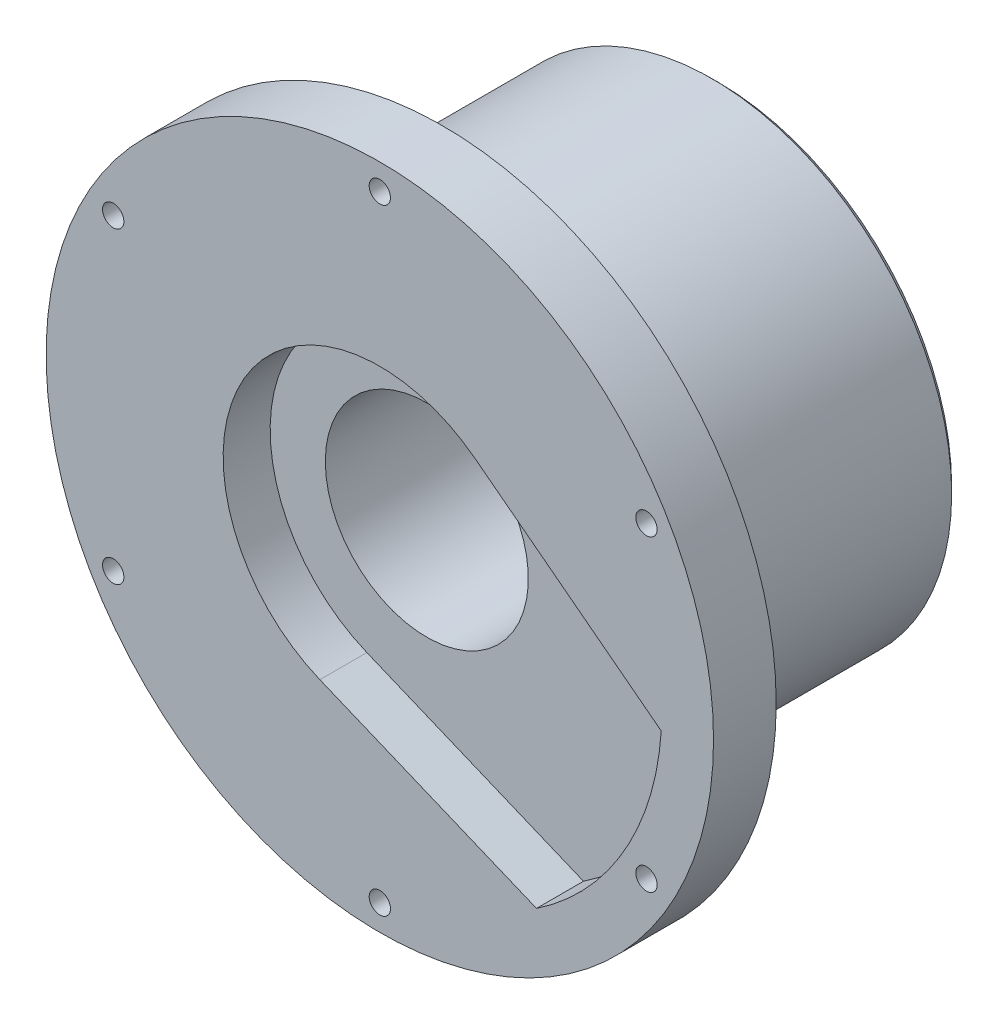
SolidWorks part; units mm, degrees
material "PLA – 15% infill – 2 walls"
ref_plane "Front Plane" through (0, 0, 0) normal (0, 0, 1) x (1, 0, 0)
ref_plane "Top Plane" through (0, 0, 0) normal (0, 1, 0) x (1, 0, 0)
ref_plane "Right Plane" through (0, 0, 0) normal (1, 0, 0) x (0, 0, -1)
sketch "Sketch1" plane through (0, 0, 0) normal (0, 0, 1) x (1, 0, 0)
  circle A0 centre (0, 0) radius 53.25
  dimension "D1" = 106.5
extrude "Boss-Extrude1" add sketch "Sketch1" along normal mid plane 54
sketch "Sketch2" plane through (0, 0, -27) normal (0, 0, -1) x (-1, 0, 0)
  circle A0 centre (0, 0) radius 38.25
  dimension "D1" = 76.5
extrude "Cut-Extrude1" cut sketch "Sketch2" against normal offset from surface (44 mm away) 10 flip side to cut up to face at (53.25, 0, 27)
sketch "Sketch3" plane through (0, 0, 27) normal (0, 0, 1) x (1, 0, 0)
  circle A0 centre (0, 0) radius 49.125 construction
  point P0 (0, 49.125)
  dimension "D1" = 98.25
hole_wizard "M3 Clearance Hole2" positions "Sketch3" profile "Sketch4" hole size "M3" standard "ANSI Metric" end condition through all
sketch "Sketch4" plane through (0, 49.125, 27) normal (1, 0, 0) x (0, -1, 0)
  line L0 (0, 0) -> (0, 54)
  line L1 (0, 54) -> (1.7, 54)
  line L2 (1.7, 54) -> (1.7, 0)
  line L5 (1.7, 0) -> (0, 0)
  line L11 (0, -6.35) -> (0, 107.95) construction
  dimension "Thru Hole Dia." = 3.4
  dimension "Thru Hole Depth" = 54
pattern_circular "CirPattern1" count 6 over 360 about axis through (0, 0, 0) along (0, 0, 1) of "M3 Clearance Hole2"
sketch "Sketch6" plane through (0, 0, 0) normal (1, 0, 0) x (0, 0, -1)
  line L0 (27, 0) -> (-27, 0)
  line L1 (27, 0) -> (27, 9.7)
  line L2 (27, -38.25) -> (27, 38.25) construction
  line L3 (27, 9.7) -> (21, 9.7)
  line L4 (21, 9.7) -> (21, 16.2)
  line L5 (21, 16.2) -> (-27, 16.2)
  line L6 (-27, 53.25) -> (-27, -53.25) construction
  line L7 (-27, 16.2) -> (-27, 0)
  dimension "D1" = 16.2
  dimension "D2" = 6
  dimension "D3" = 9.7
revolve "Cut-Revolve1" cut sketch "Sketch6" angle 360 about L0
sketch "Sketch7" plane through (0, 0, -27) normal (0, 0, -1) x (-1, 0, 0)
  circle A0 centre (0, 0) radius 13 construction
  point P27 (0, 13)
  dimension "D1" = 26
sketch "Sketch11" plane through (0, 0, 27) normal (0, 0, 1) x (1, 0, 0)
  line L1 (0, 0) -> (46.1159, -26.625) construction
  line L5 (0, 0) -> (0, 53.25) construction
  line L6 (-9.5671, -23.097) -> (25.0013, -37.4157)
  line L8 (44.9036, -2.9439) -> (15.219, 19.8338)
  line L10 (46.1159, -26.625) -> (38.9711, -22.5) construction
  arc A1 (-9.5671, -23.097) -> (15.219, 19.8338) centre (0, 0) cw
  circle A12 centre (42.5435, -24.5625) radius 1.7 construction
  circle A15 centre (42.5435, -24.5625) radius 1.7 construction
  circle A16 centre (0, 0) radius 45 construction
  circle A23 centre (0, 0) radius 25 construction
  circle A24 centre (0, 0) radius 53.25 construction
  arc A25 (25.0013, -37.4157) -> (44.9036, -2.9439) centre (0, 0) ccw
  point P11 (25.0399, -37.3899)
  point P17 (42.5435, -24.5625)
  dimension "D1" = 50
  dimension "D3" = 187.5
  dimension "D2" = 7.5
extrude "Cut-Extrude3" cut sketch "Sketch11" against normal blind 7.5
hole_wizard "M3 Clearance Hole1" positions "Sketch7" profile "Sketch8" hole size "M3" standard "ANSI Metric" end condition through all
sketch "Sketch8" plane through (0, 13, -27) normal (1, 0, 0) x (0, 1, 0)
  line L0 (0, 0) -> (0, 54)
  line L1 (0, 54) -> (1.7, 54)
  line L2 (1.7, 54) -> (1.7, 0)
  line L5 (1.7, 0) -> (0, 0)
  line L11 (0, -6.35) -> (0, 107.95) construction
  dimension "Thru Hole Dia." = 3.4
  dimension "Thru Hole Depth" = 54
sketch "Sketch13" plane through (0, 0, -27) normal (0, 0, -1) x (-1, 0, 0)
  line L0 (-3.55, 13) -> (-3.55, 9.027)
  line L1 (3.55, 13) -> (3.55, 9.027)
  circle A0 centre (0, 13) radius 1.7 construction
  circle A1 centre (0, 13) radius 1.7 construction
  circle A2 centre (0, 13) radius 3.55 construction
  circle A3 centre (0, 0) radius 9.7 construction
  arc A4 (-3.55, 9.027) -> (3.55, 9.027) centre (0, 0) cw
  arc A5 (-3.55, 13) -> (3.55, 13) centre (0, 13) cw
  dimension "D1" = 7.1
extrude "Cut-Extrude4" cut sketch "Sketch13" against normal blind 2
pattern_circular "CirPattern2" count 4 over 360 about axis through (0, 0, 0) along (0, 0, 1) of "M3 Clearance Hole1", "Cut-Extrude4"
sketch "Sketch14" plane through (0, 0, -27) normal (0, 0, -1) x (-1, 0, 0)
  line L0 (0, 9.7) -> (0, 11.7) construction
  circle A0 centre (0, 0) radius 11.7
  circle A1 centre (0, 0) radius 9.7 construction
  circle A2 centre (0, 0) radius 9.7 construction
  dimension "D1" = 2
extrude "Cut-Extrude5" cut sketch "Sketch14" against normal up to surface (2 mm away) up to face at (0, 12.0693, -25)
chamfer "Chamfer1" distance 1 angle 45 1 edges at (-38.25, 0, -27)
